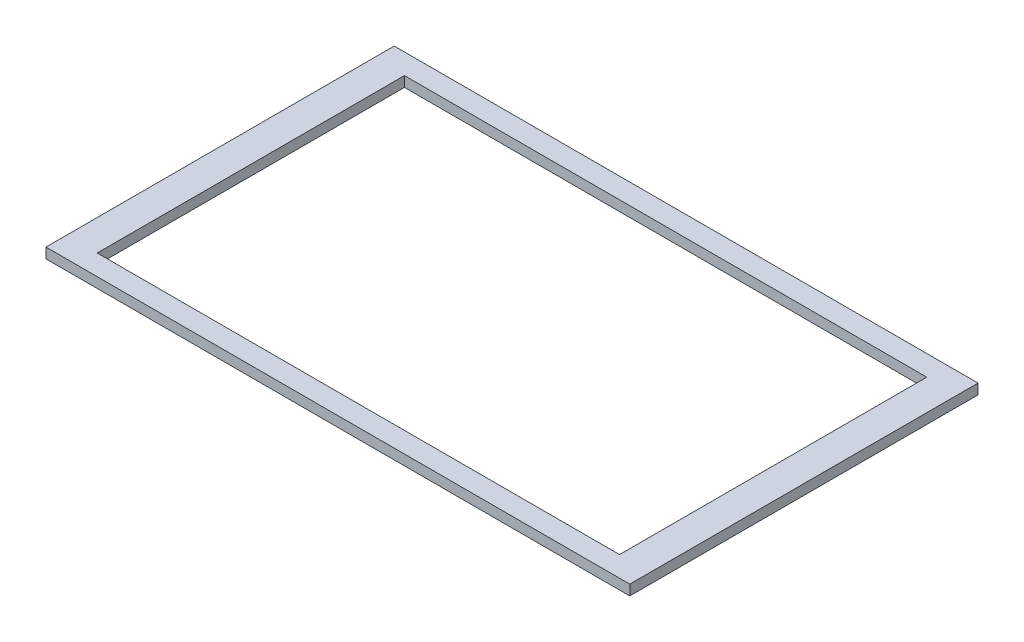
SolidWorks part; units mm, degrees
ref_plane "Plano frontal" through (0, 0, 0) normal (0, 0, 1) x (1, 0, 0)
ref_plane "Plano superior" through (0, 0, 0) normal (0, 1, 0) x (1, 0, 0)
ref_plane "Plano direito" through (0, 0, 0) normal (1, 0, 0) x (0, 0, -1)
sketch "Esboço1" plane through (0, 0, 0) normal (0, 1, 0) x (1, 0, 0)
  line L1 (-285, 170) -> (285, 170)
  line L2 (-285, 170) -> (-285, -170)
  line L3 (-285, -170) -> (285, -170)
  line L4 (285, 170) -> (285, -170)
  line L5 (-285, 170) -> (285, -170) construction
  line L6 (-285, -170) -> (285, 170) construction
  point P0 (0, 0)
  dimension "D1" = 340
  dimension "D2" = 570
extrude "Ressalto-extrusão1" add sketch "Esboço1" along normal blind 10
sketch "Esboço3" plane through (0, 10, 0) normal (0, 1, 0) x (1, 0, 0)
  line L1 (-255, 150) -> (255, 150)
  line L2 (-255, 150) -> (-255, -150)
  line L3 (-255, -150) -> (255, -150)
  line L4 (255, 150) -> (255, -150)
  line L5 (-255, 150) -> (255, -150) construction
  line L6 (-255, -150) -> (255, 150) construction
  point P0 (0, 0)
  dimension "D1" = 300
  dimension "D2" = 510
extrude "Corte-extrusão1" cut sketch "Esboço3" against normal blind 10
